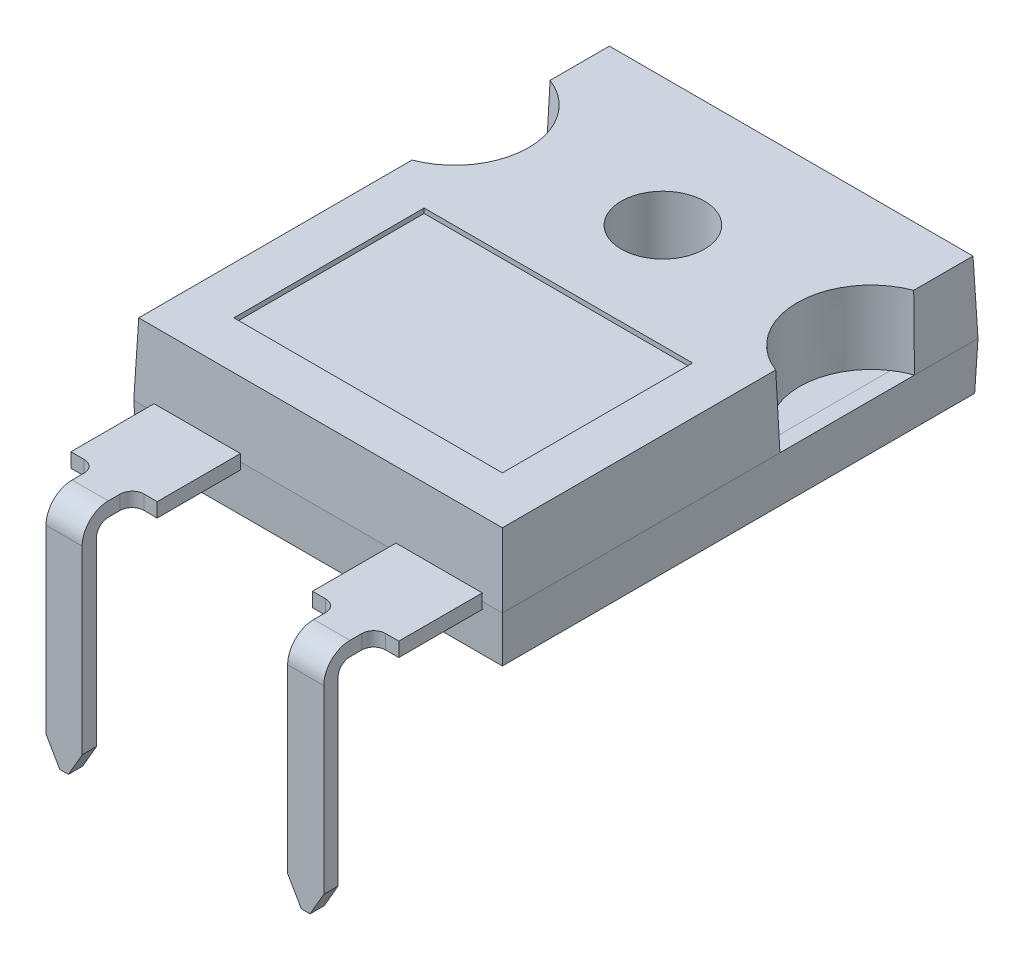
SolidWorks part; units mm, degrees
ref_plane "Front Plane" through (0, 0, 0) normal (0, 0, 1) x (1, 0, 0)
ref_plane "Top Plane" through (0, 0, 0) normal (0, 1, 0) x (1, 0, 0)
ref_plane "Right Plane" through (0, 0, 0) normal (1, 0, 0) x (0, 0, -1)
sketch "Sketch1" plane through (0, 0, 0) normal (0, 1, 0) x (1, 0, 0)
  line L1 (7.75, -14.5) -> (-7.75, -14.5)
  line L2 (7.75, -14.5) -> (7.75, 5.5)
  line L3 (7.75, 5.5) -> (-7.75, 5.5)
  line L4 (-7.75, -14.5) -> (-7.75, 5.5)
  line L5 (7.75, -14.5) -> (-7.75, 5.5) construction
  line L6 (7.75, 5.5) -> (-7.75, -14.5) construction
  circle A0 centre (0, 0) radius 1.75 construction
  point P3 (0, -4.5)
  dimension "D1" = 3.5
  dimension "D2" = 5.5
  dimension "D3" = 15.5
  dimension "D4" = 20
extrude "Extrude1" add sketch "Sketch1" against normal blind 2 draft 2
sketch "Sketch2" plane through (0, 0, 0) normal (0, 1, 0) x (1, 0, 0)
  line L0 (0, 1.75) -> (0, -1.75) construction
  line L1 (-7.75, -2.8284) -> (-7.75, -14.5)
  line L2 (7.75, 2.8284) -> (7.75, 5.5)
  line L4 (-7.75, 5.5) -> (-7.75, -14.5)
  line L5 (-7.75, -14.5) -> (7.75, -14.5)
  line L6 (7.75, -14.5) -> (7.75, 5.5)
  line L7 (7.75, 5.5) -> (-7.75, 5.5)
  line L8 (-7.75, 5.5) -> (-7.75, 2.8284)
  line L9 (-7.75, -14.5) -> (7.75, -14.5)
  line L10 (7.75, -14.5) -> (7.75, -2.8284)
  line L11 (7.75, 5.5) -> (-7.75, 5.5)
  circle A0 centre (0, 0) radius 1.75 construction
  circle A1 centre (0, 0) radius 1.75 construction
  arc A2 (-7.75, 2.8284) -> (-7.75, -2.8284) centre (-8.75, 0) cw
  arc A3 (7.75, 2.8284) -> (7.75, -2.8284) centre (8.75, 0) ccw
  dimension "D2" = 3
  dimension "D4" = 1
  dimension "D1" = 0
extrude "Extrude2" add sketch "Sketch2" along normal blind 3 draft 2
sketch "Sketch3" plane through (0, 3, 0) normal (0, 1, 0) x (1, 0, 0)
  circle A0 centre (0, 0) radius 1.75 construction
  circle A1 centre (0, 0) radius 1.75
extrude "Extrude3" cut sketch "Sketch3" against normal through all
sketch "Sketch4" plane through (0, 0, 0) normal (0, 1, 0) x (1, 0, 0)
  line L0 (-7.75, -14.5) -> (7.75, -14.5) construction
  line L1 (-7.75, -14.5) -> (7.75, -14.5) construction
  line L2 (-7.75, -14.5) -> (-7.75, -18) construction
  line L3 (-7.75, -18) -> (7.75, -18) construction
  line L4 (7.75, -18) -> (7.75, -14.5) construction
  line L5 (-6.895, -14.5) -> (-6.895, -18)
  line L6 (-3.265, -14.5) -> (-3.265, -18)
  line L7 (-6.895, -14.5) -> (-3.265, -14.5)
  line L8 (-3.265, -18) -> (-6.895, -18)
  line L9 (0, -18) -> (0, 0) construction
  line L14 (3.265, -18) -> (6.895, -18)
  line L15 (6.895, -14) -> (3.265, -14)
  line L16 (3.265, -14) -> (3.265, -18)
  line L17 (6.895, -14) -> (6.895, -18)
  point P8 (5.08, -18)
  point P18 (-5.08, -18)
  dimension "D1" = 3.5
  dimension "D2" = 3.63
  dimension "D3" = 5.08
  dimension "D4" = 5.08
extrude "Extrude4" add sketch "Sketch4" along normal mid plane 0.6
sketch "Sketch5" plane through (0, 3, 0) normal (0, 1, 0) x (1, 0, 0)
  line L0 (-7.6452, -2.9016) -> (-7.6452, -14.3952) construction
  line L1 (5.6452, -12.3952) -> (-5.6452, -12.3952)
  line L2 (5.6452, -12.3952) -> (5.6452, -4.3952)
  line L3 (5.6452, -4.3952) -> (-5.6452, -4.3952)
  line L4 (-5.6452, -12.3952) -> (-5.6452, -4.3952)
  line L5 (5.6452, -12.3952) -> (-5.6452, -4.3952) construction
  line L6 (5.6452, -4.3952) -> (-5.6452, -12.3952) construction
  line L7 (-7.6452, -14.3952) -> (7.6452, -14.3952) construction
  point P0 (0, -8.3952)
  dimension "D1" = 2
  dimension "D2" = 2
  dimension "D3" = 8
extrude "Extrude5" cut sketch "Sketch5" against normal blind 0.2
sketch "Sketch6" plane through (0, 0, 18) normal (0, 0, 1) x (1, 0, 0)
  line L1 (-5.08, 0) -> (0, 0) construction
  line L2 (0, 0) -> (5.08, 0) construction
  line L7 (5.84, -0.3) -> (4.32, -0.3) construction
  line L8 (5.84, -0.3) -> (5.84, 0.3) construction
  line L9 (5.84, 0.3) -> (4.32, 0.3) construction
  line L10 (4.32, -0.3) -> (4.32, 0.3) construction
  line L11 (-4.32, -0.3) -> (-5.84, -0.3)
  line L12 (-4.32, -0.3) -> (-4.32, 0.3)
  line L13 (-4.32, 0.3) -> (-5.84, 0.3)
  line L14 (-5.84, -0.3) -> (-5.84, 0.3)
  line L15 (-4.32, -0.3) -> (-5.84, 0.3) construction
  line L16 (-4.32, 0.3) -> (-5.84, -0.3) construction
  line L17 (5.84, -0.3) -> (4.32, 0.3) construction
  line L18 (5.84, 0.3) -> (4.32, -0.3) construction
  point P9 (-5.5, 0)
  point P10 (5.5, 0)
  dimension "D1" = 5.08
  dimension "D2" = 5.08
sketch3d "3DSketch1"
  line L0 (-5.5, 0, 18) -> (-5.5, 0, 19)
  line L1 (-5.5, 0, 19) -> (-5.5, -0.8, 19) construction
  line L4 (-5.5, -0.8, 19.8) -> (-5.5, -9.4, 19.8)
  line L5 (-5.5, -0.8, 19) -> (-5.5, -0.8, 19.8) construction
  arc A0 (-5.5, 0, 19) -> (-5.5, -0.8, 19.8) centre (-5.5, -0.8, 19) ccw
  point P4 (0, 0, 0)
  point P5 (0, 0, 0)
  point P6 (-4.7, -0.8, 19)
  point P8 (0, 0, 0)
  dimension "D1" = 0.8
  dimension "D2" = 8.6
  dimension "D3" = 1
sweep "Sweep1" add profiles "Sketch6" path "3DSketch1"
chamfer "Chamfer1" distance 1 angle 30 2 edges at (-5.84, -9.4, 19.8) (-4.32, -9.4, 19.8)
pattern_linear "LPattern1" count 2 spacing 10.16 along (1, 0, 0) of "Sweep1", "Chamfer1"
sketch "Sketch7" plane through (0, -2, 0) normal (0, -1, 0) x (1, 0, 0)
  line L8 (-7.0802, 13.8302) -> (-7.0802, -4.8302)
  line L9 (-7.0802, -4.8302) -> (7.0802, -4.8302)
  line L10 (7.0802, -4.8302) -> (7.0802, 13.8302)
  line L11 (7.0802, 13.8302) -> (-7.0802, 13.8302)
  line L12 (-7.0802, 12.8302) -> (-7.0802, -3.8302)
  line L13 (-6.0802, -4.8302) -> (6.0802, -4.8302)
  line L14 (7.0802, -3.8302) -> (7.0802, 12.8302)
  line L15 (6.0802, 13.8302) -> (-6.0802, 13.8302)
  arc A0 (-7.0802, 12.8302) -> (-6.0802, 13.8302) centre (-6.0802, 12.8302) cw
  arc A1 (-7.0802, -3.8302) -> (-6.0802, -4.8302) centre (-6.0802, -3.8302) ccw
  arc A2 (6.0802, -4.8302) -> (7.0802, -3.8302) centre (6.0802, -3.8302) ccw
  arc A3 (7.0802, 12.8302) -> (6.0802, 13.8302) centre (6.0802, 12.8302) ccw
  circle A6 centre (0, 0) radius 3.25
  circle A7 centre (0, 0) radius 3.25
  dimension "D2" = 1
  dimension "D1" = 0.6
  dimension "D3" = 1.5
extrude "Cut-Extrude1" cut sketch "Sketch7" against normal up to surface (2 mm away) up to face at (7.75, 0, 2.8284)
sketch "Sketch8" plane through (0, -2, 0) normal (0, -1, 0) x (1, 0, 0)
  line L4 (-7.0802, 12.8302) -> (-7.0802, -3.8302)
  line L5 (-6.0802, -4.8302) -> (6.0802, -4.8302)
  line L6 (7.0802, -3.8302) -> (7.0802, 12.8302)
  line L7 (6.0802, 13.8302) -> (-6.0802, 13.8302)
  line L8 (-7.0802, 12.8302) -> (-7.0802, -3.8302)
  line L9 (-6.0802, -4.8302) -> (6.0802, -4.8302)
  line L10 (7.0802, -3.8302) -> (7.0802, 12.8302)
  line L11 (6.0802, 13.8302) -> (-6.0802, 13.8302)
  circle A1 centre (0, 0) radius 3.25
  circle A2 centre (0, 0) radius 3.25
  arc A4 (-7.0802, -3.8302) -> (-6.0802, -4.8302) centre (-6.0802, -3.8302) ccw
  arc A5 (6.0802, -4.8302) -> (7.0802, -3.8302) centre (6.0802, -3.8302) ccw
  arc A6 (7.0802, 12.8302) -> (6.0802, 13.8302) centre (6.0802, 12.8302) ccw
  arc A7 (-6.0802, 13.8302) -> (-7.0802, 12.8302) centre (-6.0802, 12.8302) ccw
  arc A8 (-7.0802, -3.8302) -> (-6.0802, -4.8302) centre (-6.0802, -3.8302) ccw
  arc A9 (6.0802, -4.8302) -> (7.0802, -3.8302) centre (6.0802, -3.8302) ccw
  arc A10 (7.0802, 12.8302) -> (6.0802, 13.8302) centre (6.0802, 12.8302) ccw
  arc A11 (-6.0802, 13.8302) -> (-7.0802, 12.8302) centre (-6.0802, 12.8302) ccw
  dimension "D1" = 0
  dimension "D2" = 0
extrude "Extrude7" add sketch "Sketch8" against normal up to surface (2 mm away) separate body up to face at (7.4151, 0, 0.7911)
fillet "Fillet2" radius 0.5 2 edges
fillet "Fillet3" radius 0.5 2 edges
equation "\"R1\"=0.509309"
